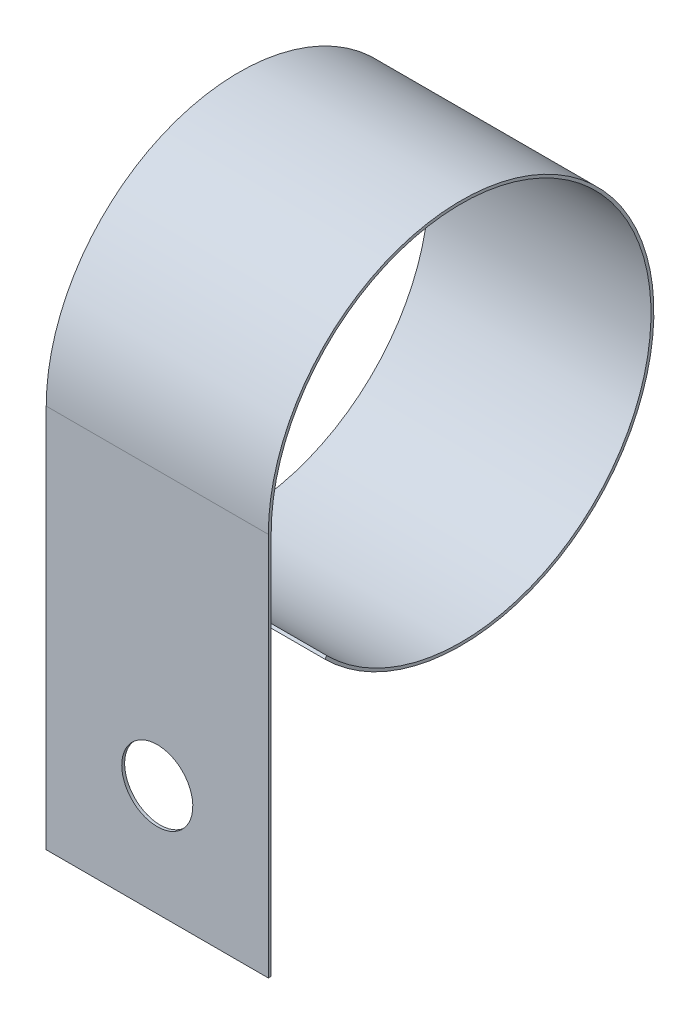
SolidWorks part; units mm, degrees
material "SUS304"
ref_plane "Front Plane" through (0, 0, 0) normal (0, 0, 1) x (1, 0, 0)
ref_plane "Top Plane" through (0, 0, 0) normal (0, 1, 0) x (1, 0, 0)
ref_plane "Right Plane" through (0, 0, 0) normal (1, 0, 0) x (0, 0, -1)
sketch "Sketch1" plane through (0, 0, 0) normal (1, 0, 0) x (0, -1, 0)
  line L7 (0, 0) -> (0, -8.55) construction
  line L8 (6.1377, -6.1377) -> (0, 0) construction
  line L9 (6.1377, -6.1377) -> (6.0458, -6.0458)
  line L10 (17.3, -8.68) -> (0, -8.68)
  line L11 (17.3, -8.55) -> (17.3, -8.68)
  line L12 (17.3, -8.55) -> (0, -8.55)
  circle A3 centre (0, 0) radius 8.55 construction
  arc A4 (0, -8.68) -> (6.1377, -6.1377) centre (0, 0) cw
  arc A5 (0, -8.55) -> (6.0458, -6.0458) centre (0, 0) cw
  dimension "MSM_1" = 17.1
  dimension "MSM_5" = 17.3
  dimension "FIX_1" = 45
  dimension "Accessories Plate Thickness" = 0.13
extrude "Boss-Extrude1" add sketch "Sketch1" along normal mid plane 10
sketch "Sketch2" plane through (0, 0, 8.68) normal (0, 0, -1) x (-1, 0, 0)
  circle A0 centre (0, -12.3) radius 1.6
  dimension "D_s" = 3.2
  dimension "Y" = 5
extrude "Cut-Extrude1" cut sketch "Sketch2" along normal up to next
